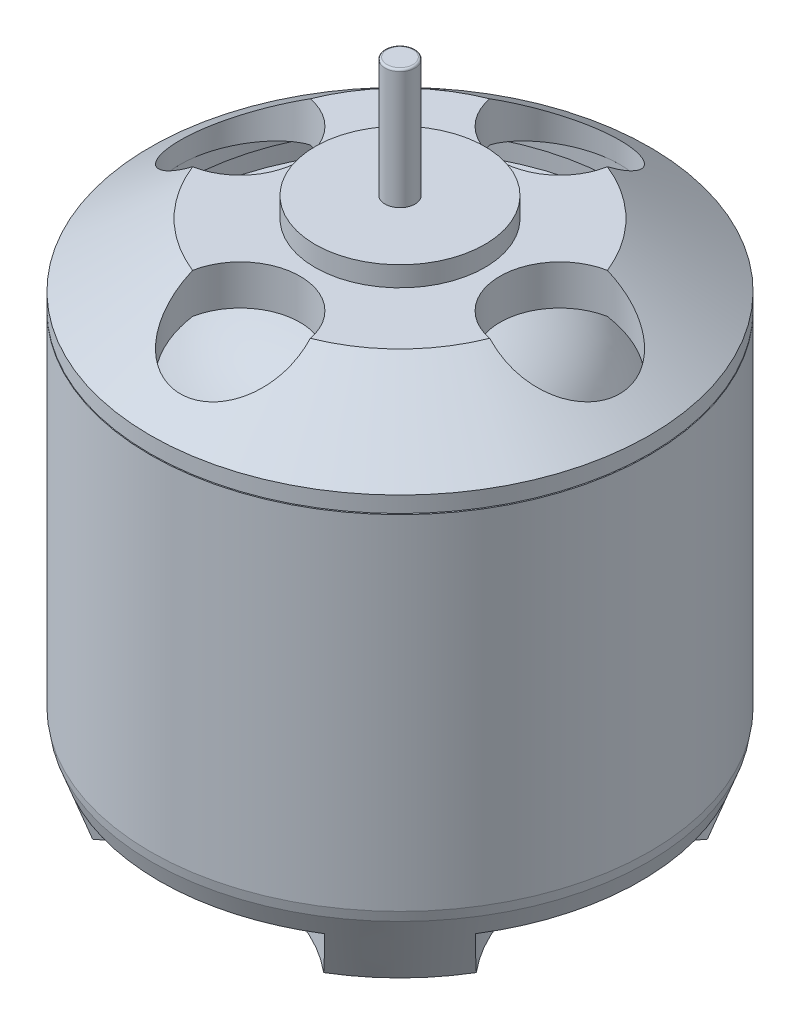
SolidWorks part; units mm, degrees
ref_plane "Front Plane" through (0, 0, 0) normal (0, 0, 1) x (1, 0, 0)
ref_plane "Top Plane" through (0, 0, 0) normal (0, 1, 0) x (1, 0, 0)
ref_plane "Right Plane" through (0, 0, 0) normal (1, 0, 0) x (0, 0, -1)
sketch "Sketch1" plane through (0, 0, 0) normal (0, 0, 1) x (1, 0, 0)
  line L0 (0, 31.9244) -> (0, -7.5455) construction
  line L1 (-17.542, 0) -> (19.5028, 0) construction
  line L2 (0.75, -1.8) -> (9.6564, -1.8)
  line L3 (9.6564, -1.8) -> (10.9118, -0.5)
  line L4 (10.9118, -0.5) -> (11, 0)
  line L5 (11, 0) -> (12.5, 0)
  line L6 (12.5, 0) -> (12.4118, -0.5)
  line L7 (12.4118, -0.5) -> (11.2107, -3.8)
  line L8 (0.75, -1.8) -> (0.75, -3.3172)
  line L9 (0.75, -3.3172) -> (3, -3.3172)
  line L10 (3, -3.3172) -> (3.5, -3.8)
  line L11 (3.5, -3.8) -> (11.2107, -3.8)
  line L12 (12.5, 0) -> (12.5, 17.2491) construction
  line L13 (11, 0) -> (11, 17.2491) construction
  line L14 (11, 17.2491) -> (12.5, 17.2491)
  line L15 (12.5, 17.2491) -> (12.5, 18.0491)
  line L16 (12.5, 18.0491) -> (8, 21.2)
  line L17 (8, 21.2) -> (4.25, 21.2)
  line L18 (4.25, 21.2) -> (4.25, 22.2)
  line L19 (4.25, 22.2) -> (0.75, 22.2)
  line L20 (0.75, 22.2) -> (0.75, 19.2)
  line L21 (0.75, 19.2) -> (8, 19.2)
  line L22 (8, 19.2) -> (11, 18.0491)
  line L23 (11, 18.0491) -> (11, 17.2491)
  dimension "D1" = 25
  dimension "D2" = 2
  dimension "D3" = 1.8
  dimension "D4" = 110
  dimension "D5" = 170
  dimension "D6" = 0.5
  dimension "D7" = 44
  dimension "D8" = 1.5
  dimension "D9" = 6
  dimension "D10" = 7
  dimension "D11" = 1.5
  dimension "D12" = 25
  dimension "D13" = 2
  dimension "D14" = 1
  dimension "D15" = 3.5
  dimension "D16" = 1.5
  dimension "D17" = 35
  dimension "D18" = 0.8
  dimension "D19" = 16
revolve "Revolve1" add sketch "Sketch1" angle 360 about L0
sketch "Sketch2" plane through (0, -3.8, 0) normal (0, -1, 0) x (1, 0, 0)
  line L0 (0, 0) -> (14.4306, 14.4306) construction
  circle A0 centre (0, 0) radius 12.4118 construction
  arc A1 (-6.6756, 10.4637) -> (-10.4637, 6.6756) centre (0, 0) ccw
  arc A3 (10.4637, 6.6756) -> (10.4637, -6.6756) centre (16.5, 0) ccw
  arc A4 (6.6756, -10.4637) -> (-6.6756, -10.4637) centre (0, -16.5) ccw
  arc A5 (-10.4637, -6.6756) -> (-10.4637, 6.6756) centre (-16.5, 0) ccw
  arc A6 (-6.6756, 10.4637) -> (6.6756, 10.4637) centre (0, 16.5) ccw
  arc A7 (10.4637, 6.6756) -> (6.6756, 10.4637) centre (0, 0) ccw
  arc A8 (6.6756, -10.4637) -> (10.4637, -6.6756) centre (0, 0) ccw
  arc A9 (-10.4637, -6.6756) -> (-6.6756, -10.4637) centre (0, 0) ccw
  circle A10 centre (5.3033, 5.3033) radius 1.25
  circle A11 centre (5.3033, -5.3033) radius 1.25
  circle A12 centre (-5.3033, -5.3033) radius 1.25
  circle A13 centre (-5.3033, 5.3033) radius 1.25
  point P15 (0, 0)
  point P27 (0, 0)
  dimension "D2" = 2.5
  dimension "D3" = 18
  dimension "D4" = 7.5
  dimension "D1" = 4
  dimension "D5" = 4
extrude "Cut-Extrude2" cut sketch "Sketch2" against normal blind 2.3 flip side to cut
cosmetic thread "Cosmetic Thread1" parameters "D2"=2.87
cosmetic thread "Cosmetic Thread2" parameters "D2"=2.87
cosmetic thread "Cosmetic Thread3" parameters "D2"=2.87
cosmetic thread "Cosmetic Thread4" parameters "D2"=2.87
sketch "Sketch3" plane through (0, 21.2, 0) normal (0, 1, 0) x (1, 0, 0)
  circle A0 centre (8, 0) radius 3
  circle A1 centre (0, 0) radius 8 construction
  circle A3 centre (0, -8) radius 3
  circle A4 centre (-8, 0) radius 3
  circle A5 centre (0, 8) radius 3
  point P13 (0, 0)
  dimension "D1" = 6
  dimension "D2" = 4
extrude "Cut-Extrude3" cut sketch "Sketch3" against normal up to next
sketch "Sketch4" plane through (0, 0, 0) normal (0, 0, 1) x (1, 0, 0)
  line L1 (12.5, 17.2) -> (11.5, 17.2)
  line L2 (12.5, 17.2) -> (12.5, 0)
  line L3 (12.5, 0) -> (11.5, 0)
  line L4 (11.5, 17.2) -> (11.5, 0)
  line L5 (12.5, 0) -> (-12.5, 0) construction
  line L6 (0, 33.9885) -> (0, -11.7025) construction
  line L7 (0.75, 28.2) -> (0, 28.2)
  line L8 (0.75, 28.2) -> (0.75, -4.8)
  line L9 (0.75, -4.8) -> (0, -4.8)
  line L10 (0, 28.2) -> (0, -4.8)
  line L11 (4.25, 22.2) -> (-4.25, 22.2) construction
  dimension "D1" = 33
  dimension "D2" = 6
  dimension "D3" = 0.75
  dimension "D4" = 1
  dimension "D5" = 12.5
  dimension "D6" = 17.2
revolve "Revolve3" add sketch "Sketch4" angle 360 about L6
sketch "Sketch5" plane through (0, 0, 0) normal (0, 0, 1) x (1, 0, 0)
  line L0 (0, 36.9242) -> (0, -8.9622) construction
  line L1 (0.75, -0.8) -> (0.75, 18.7)
  line L2 (0.75, 18.7) -> (1.75, 18.7)
  line L3 (1.75, 18.7) -> (1.75, 0.4)
  line L4 (0.75, -0.8) -> (5.75, -0.8)
  line L5 (5.75, -0.8) -> (5.75, 0.4)
  line L6 (5.75, 0.4) -> (1.75, 0.4)
  line L7 (-2.9468, 19.2) -> (2.9468, 19.2) construction
  line L8 (8.6211, -1.8) -> (4.3501, -1.8) construction
  dimension "D1" = 1.5
  dimension "D2" = 1
  dimension "D3" = 1.2
  dimension "D4" = 1
  dimension "D5" = 0.5
  dimension "D6" = 4
revolve "Revolve4" add sketch "Sketch5" angle 360 about L0
sketch "Sketch6" plane through (0, 0, 0) normal (0, 0, 1) x (1, 0, 0)
  line L0 (5.75, 0.4) -> (1.75, 0.4) construction
  line L1 (2.8782, 0.4) -> (4.6312, 0.4) construction
  line L2 (1.75, 18.7) -> (1.75, 0.4)
  line L3 (1.75, 0.4) -> (3.75, 0.4)
  line L4 (11.5, 17.2) -> (-11.5, 17.2) construction
  spline S0 degree 3 poles (1.75, 18.7) (2.3068, 19.2321) (11.0427, 18.6521) (9.5024, 6.4382) (7.3258, 2.7871) (4.6349, 0.4) (3.75, 0.4) knots 0 0 0 0 0.314782 0.817368 0.88589 1 1 1 1
revolve "Revolve6" add sketch "Sketch6" angle 360 about L0
fillet "Fillet1" radius 0.1 2 edges at (0, 28.2, 0.75) (0, -4.8, 0.75)
sketch "Sketch7" plane through (0, 0, 0) normal (0, 0, 1) x (1, 0, 0)
  line L0 (0, 32.5499) -> (0, 0) construction
  line L1 (10, 16) -> (11.5, 16)
  line L2 (10, 16) -> (10, 1)
  line L3 (10, 1) -> (11.5, 1)
  line L4 (11.5, 16) -> (11.5, 1)
  dimension "D1" = 10
  dimension "D2" = 11.5
  dimension "D3" = 15
  dimension "D4" = 1
revolve "Revolve7" add sketch "Sketch7" angle 360 about L0
sketch "Sketch9" plane through (0, -0.8, 0) normal (0, -1, 0) x (1, 0, 0)
  line L1 (-9, -3.5) -> (0, -3.5)
  line L3 (-9, 3.5) -> (0, 3.5)
  line L4 (0, -3.5) -> (0, 3.5)
  arc A0 (-9, -3.5) -> (-9, 3.5) centre (-0.7084, 0) cw
  point P4 (0, 0)
  dimension "D3" = 9
  dimension "D1" = 9
  dimension "D2" = 7
extrude "Boss-Extrude1" add sketch "Sketch9" along normal up to surface (1 mm away) up to face at (5.3033, -1.8, -6.5533)
sketch "Sketch10" plane through (0, -1.8, 0) normal (0, -1, 0) x (1, 0, 0)
  line L1 (-12.5, 4.5) -> (-9, 4.5)
  line L2 (-12.5, 4.5) -> (-12.5, -4.5)
  line L3 (-12.5, -4.5) -> (-9, -4.5)
  line L4 (-9, 4.5) -> (-9, -4.5)
  point P4 (-9, 0)
  dimension "D1" = 9
  dimension "D2" = 9
  dimension "D3" = 3.5
extrude "Boss-Extrude2" add sketch "Sketch10" along normal blind 1.5
